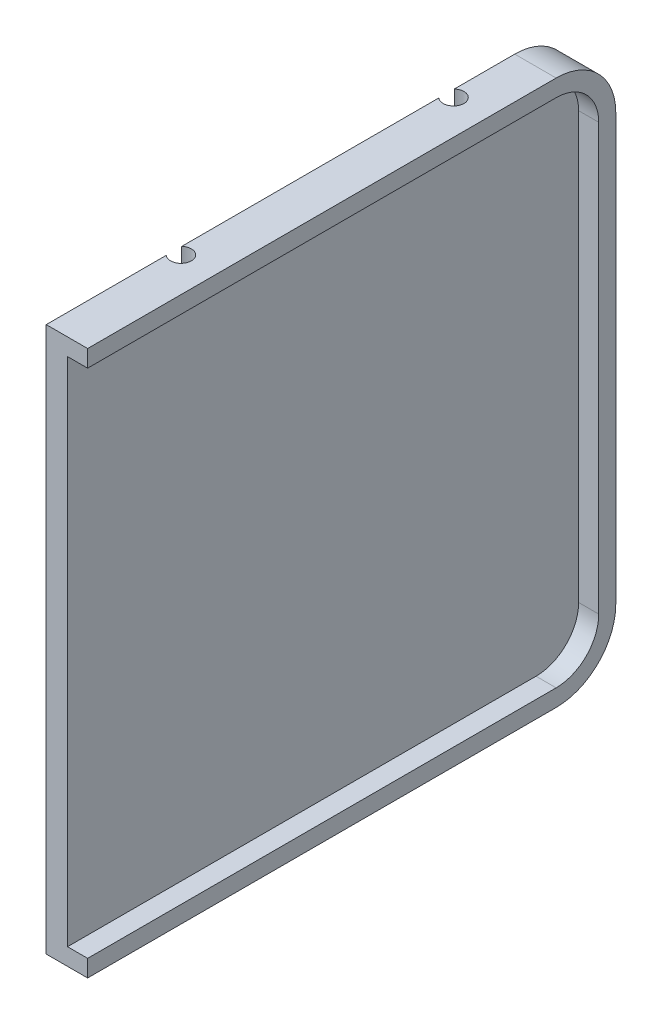
SolidWorks part; units mm, degrees
ref_plane "Front Plane" through (0, 0, 0) normal (0, 0, 1) x (1, 0, 0)
ref_plane "Top Plane" through (0, 0, 0) normal (0, 1, 0) x (1, 0, 0)
ref_plane "Right Plane" through (0, 0, 0) normal (1, 0, 0) x (0, 0, -1)
sketch "Sketch1" plane through (35.1028, 0, 0) normal (-1, 0, 0) x (0, 0, 1)
  line L0 (-114.3, 38.1) -> (-114.3, -38.1)
  line L1 (-114.3, 38.1) -> (-184.15, 38.1)
  line L2 (-190.5, 31.75) -> (-190.5, -31.75)
  line L3 (-184.15, -38.1) -> (-114.3, -38.1)
  line L4 (190.5, -31.75) -> (190.5, 31.75)
  line L5 (184.15, 38.1) -> (-184.15, 38.1)
  line L6 (-190.5, 31.75) -> (-190.5, -31.75)
  line L7 (-184.15, -38.1) -> (184.15, -38.1)
  line L8 (190.5, -31.75) -> (190.5, 31.75) construction
  line L9 (184.15, 38.1) -> (-184.15, 38.1) construction
  line L10 (-190.5, 31.75) -> (-190.5, -31.75) construction
  line L11 (-184.15, -38.1) -> (184.15, -38.1) construction
  arc A0 (-190.5, -31.75) -> (-184.15, -38.1) centre (-184.15, -31.75) ccw
  arc A1 (-190.5, 31.75) -> (-184.15, 38.1) centre (-184.15, 31.75) cw
  arc A4 (184.15, -38.1) -> (190.5, -31.75) centre (184.15, -31.75) ccw
  arc A5 (190.5, 31.75) -> (184.15, 38.1) centre (184.15, 31.75) ccw
  arc A6 (-184.15, 38.1) -> (-190.5, 31.75) centre (-184.15, 31.75) ccw
  arc A7 (-190.5, -31.75) -> (-184.15, -38.1) centre (-184.15, -31.75) ccw
  arc A8 (184.15, -38.1) -> (190.5, -31.75) centre (184.15, -31.75) ccw construction
  arc A9 (190.5, 31.75) -> (184.15, 38.1) centre (184.15, 31.75) ccw construction
  arc A10 (-184.15, 38.1) -> (-190.5, 31.75) centre (-184.15, 31.75) ccw construction
  arc A11 (-190.5, -31.75) -> (-184.15, -38.1) centre (-184.15, -31.75) ccw construction
  dimension "D2" = 76.2
  dimension "D1" = 0
extrude "Boss-Extrude1" add sketch "Sketch1" along normal blind 3.175 contours L0 L3 A0 L2 A1 L1
ref_plane "Plane1" through (35.1028, 38.1, -184.15) normal (0, 0, -1) x (-1, 0, 0)
sketch "Sketch4" plane through (31.9278, 0, 0) normal (-1, 0, 0) x (0, 0, 1)
  line L4 (-114.3, 38.1) -> (-184.15, 38.1)
  line L5 (-190.5, 31.75) -> (-190.5, -31.75)
  line L6 (-184.15, -38.1) -> (-114.3, -38.1)
  line L7 (-114.3, -38.1) -> (-114.3, 38.1)
  line L8 (-114.3, 38.1) -> (-184.15, 38.1)
  line L9 (-190.5, 31.75) -> (-190.5, -31.75)
  line L10 (-184.15, -38.1) -> (-114.3, -38.1)
  line L11 (-114.3, -38.1) -> (-114.3, 38.1) construction
  arc A2 (-184.15, 38.1) -> (-190.5, 31.75) centre (-184.15, 31.75) ccw
  arc A3 (-190.5, -31.75) -> (-184.15, -38.1) centre (-184.15, -31.75) ccw
  arc A4 (-184.15, 38.1) -> (-190.5, 31.75) centre (-184.15, 31.75) ccw
  arc A5 (-190.5, -31.75) -> (-184.15, -38.1) centre (-184.15, -31.75) ccw
  dimension "D1" = 0
extrude "Extrude-Thin1" add sketch "Sketch4" against normal up to surface (6.1722 mm away) thin
sketch "Sketch5" plane through (31.9278, 0, 0) normal (-1, 0, 0) x (0, 0, 1)
  line L0 (-193.04, 25.4) -> (-114.3, 25.4) construction
  line L1 (-193.04, -25.4) -> (-114.3, -25.4) construction
  line L2 (-114.3, -25.4) -> (-114.3, 25.4) construction
  line L3 (-114.3, 40.64) -> (-114.3, -40.64) construction
  line L4 (-193.04, 31.75) -> (-193.04, -31.75) construction
  line L5 (-114.3, 0) -> (-193.04, 0) construction
  circle A0 centre (-186.69, 33.075) radius 4.5 construction
  circle A1 centre (-120.65, 33.075) radius 4.5 construction
  circle A2 centre (-120.65, -33.075) radius 4.5 construction
  circle A3 centre (-186.69, -33.075) radius 4.5 construction
  circle A4 centre (-186.69, 33.075) radius 1.475
  circle A5 centre (-120.65, 33.075) radius 1.475
  circle A6 centre (-120.65, -33.075) radius 1.475
  circle A7 centre (-186.69, -33.075) radius 1.475
  point P4 (-114.3, 0)
  point P11 (-186.69, 28.575)
  dimension "D2" = 9
  dimension "D6" = 2.95
  dimension "D1" = 50.8
  dimension "D3" = 3.175
  dimension "D4" = 6.35
  dimension "D5" = 6.35
extrude "Boss-Extrude2" add sketch "Sketch5" along normal blind 5
sketch "Sketch6" plane through (0, 40.64, 0) normal (0, 1, 0) x (1, 0, 0)
  line L1 (31.9278, 114.3) -> (31.9278, 184.15) construction
  line L2 (38.1, 193.04) -> (31.9278, 193.04) construction
  line L3 (38.1, 114.3) -> (31.9278, 114.3) construction
  circle A0 centre (32.9698, 173.99) radius 1.55
  circle A1 centre (32.9698, 133.35) radius 1.55
  point P4 (0, 0)
  point P6 (31.4198, 173.99)
  point P8 (0, 0)
  dimension "D1" = 3.1
  dimension "D2" = 0.508
  dimension "D3" = 19.05
  dimension "D4" = 19.05
extrude "Cut-Extrude1" cut sketch "Sketch6" against normal through all
chamfer "Chamfer1" distance 0.508 angle 45 4 edges at (26.9278, -33.075, -188.165) (26.9278, -33.075, -122.125) (26.9278, 33.075, -119.175) (26.9278, 33.075, -185.215)
sketch "Sketch7" plane through (31.9278, 0, 0) normal (-1, 0, 0) x (0, 0, 1)
  circle A0 centre (-186.69, 33.075) radius 2.5
  circle A1 centre (-120.65, 33.075) radius 2.5
  circle A2 centre (-120.65, -33.075) radius 2.5
  circle A3 centre (-186.69, -33.075) radius 2.5
  dimension "D1" = 5
extrude "Boss-Extrude3" add sketch "Sketch7" along normal blind 0.254
